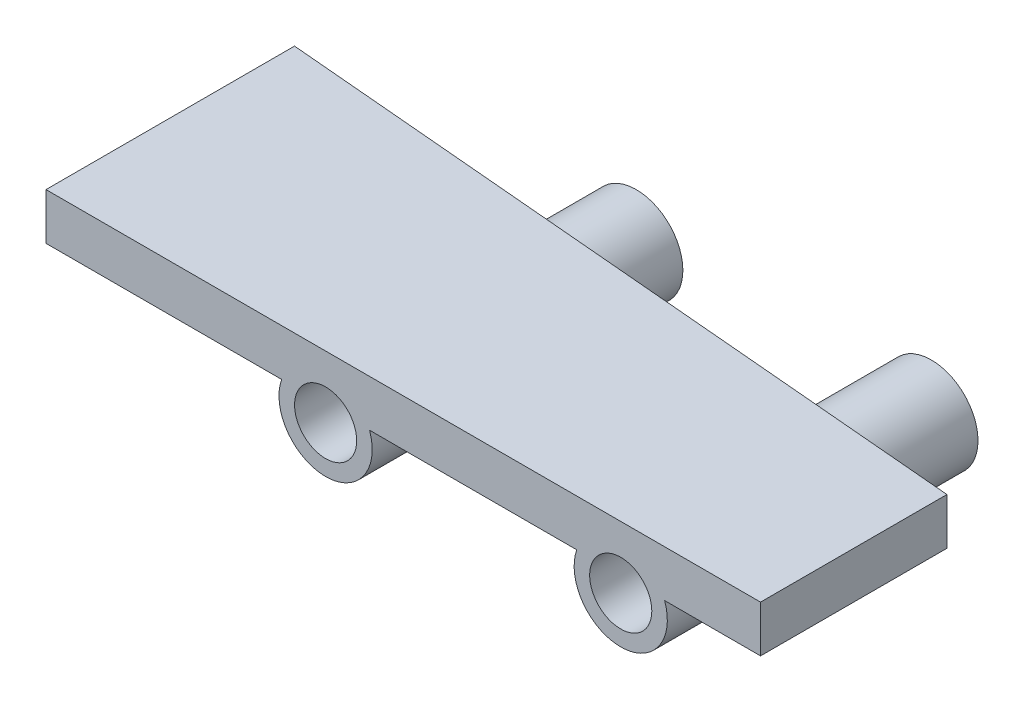
SolidWorks part; units mm, degrees
ref_plane "Front Plane" through (0, 0, 0) normal (0, 0, 1) x (1, 0, 0)
ref_plane "Top Plane" through (0, 0, 0) normal (0, 1, 0) x (1, 0, 0)
ref_plane "Right Plane" through (0, 0, 0) normal (1, 0, 0) x (0, 0, -1)
sketch "Sketch1" plane through (0, 0, 0) normal (0, 1, 0) x (1, 0, 0)
  line L0 (0, 101.6) -> (292.1, 76.2)
  line L1 (0, 0) -> (292.1, 0)
  line L2 (0, 0) -> (0, 101.6)
  line L3 (0, 101.6) -> (292.1, 101.6)
  line L4 (292.1, 0) -> (292.1, 101.6)
  dimension "D1" = 292.1
  dimension "D2" = 101.6
  dimension "D3" = 25.4
extrude "Boss-Extrude1" add sketch "Sketch1" along normal blind 19.05 contours L1 L4 L0 L2
sketch "Sketch6" plane through (0, 0, 0) normal (0, 0, 1) x (1, 0, 0)
  line L1 (0, 19.05) -> (0, 0) construction
  line L3 (0, 19.05) -> (292.1, 19.05) construction
  circle A0 centre (114.3, -6.35) radius 12.7
  circle A1 centre (234.95, -6.35) radius 12.7
  circle A2 centre (114.3, -6.35) radius 19.05
  circle A3 centre (234.95, -6.35) radius 19.05
  dimension "D1" = 25.4
  dimension "D5" = 38.1
  dimension "D2" = 114.3
  dimension "D3" = 120.65
  dimension "D4" = 25.4
extrude "Boss-Extrude3" add sketch "Sketch6" against normal blind 127
sketch "Sketch7" plane through (0, 0, 0) normal (0, 0, 1) x (1, 0, 0)
  circle A0 centre (114.3, -6.35) radius 12.7
  circle A1 centre (234.95, -6.35) radius 12.7
extrude "Cut-Extrude1" cut sketch "Sketch7" against normal up to surface (90.5565 mm away)
sketch "Sketch8" plane through (0, 0, 0) normal (0, -1, 0) x (1, 0, 0)
  line L0 (0, -25.4) -> (292.1, -25.4)
  line L1 (292.1, -25.4) -> (292.1, -50.7042)
  line L5 (0, -76.1042) -> (292.1, -50.7042)
  line L6 (0, -101.6) -> (96.3395, -93.2227) construction
  line L7 (0, 0) -> (96.3395, 0) construction
  line L9 (292.1, 0) -> (292.1, -76.2) construction
  line L10 (0, -25.4) -> (0, -76.1042)
  line L11 (0, -25.4) -> (0, -76.1042)
  line L12 (292.1, -50.7042) -> (292.1, -25.4)
  line L13 (0, -25.4) -> (292.1, -25.4)
  line L14 (0, -76.1042) -> (292.1, -50.7042)
  line L15 (292.1, -25.4) -> (292.1, -50.7042)
  line M8 (132.2605, 0) -> (132.2605, -90.0991)
  line M10 (216.9895, -82.7313) -> (216.9895, 0)
  dimension "D1" = 25.4
  dimension "D2" = 25.4
extrude "Cut-Extrude2" cut sketch "Sketch8" along normal through all contours L0 L10 L5 M8 | L5 L0 M8 M10 | L5 L1 L0 M10
